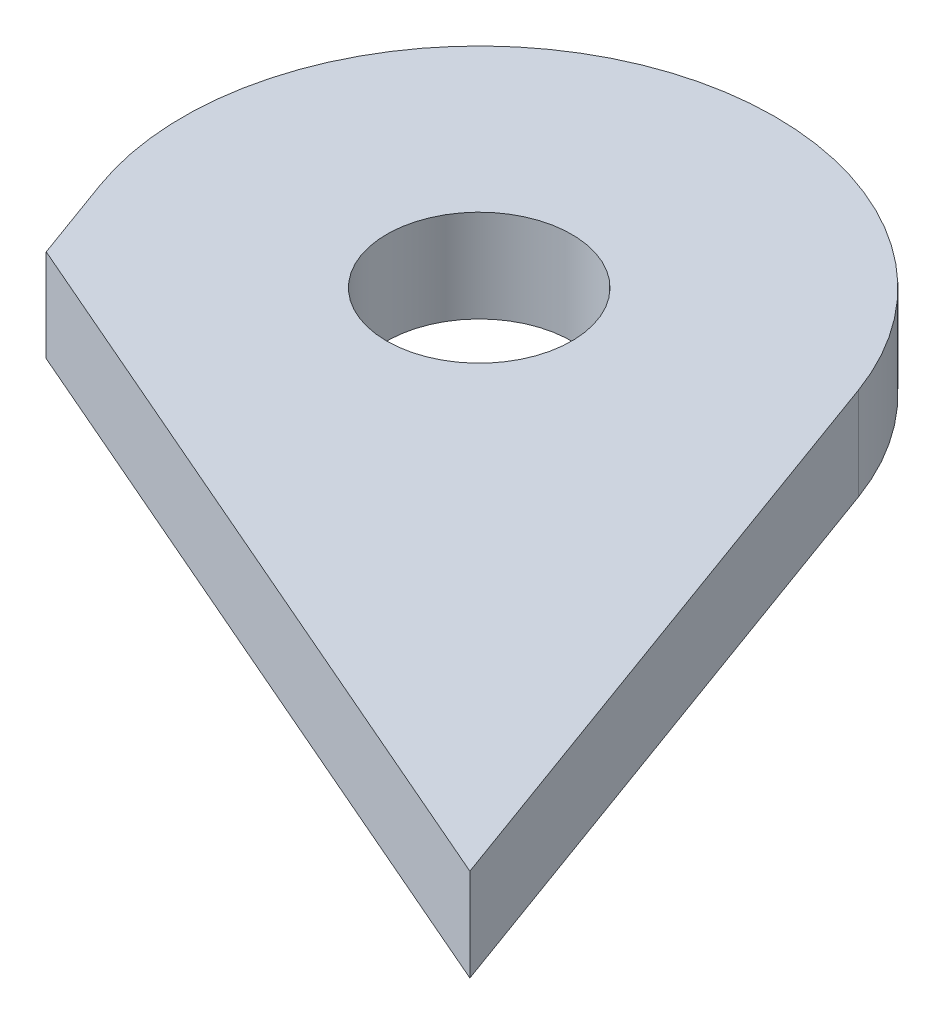
SolidWorks part; units mm, degrees
ref_plane "Front Plane" through (0, 0, 0) normal (0, 0, 1) x (1, 0, 0)
ref_plane "Top Plane" through (0, 0, 0) normal (0, 1, 0) x (1, 0, 0)
ref_plane "Right Plane" through (0, 0, 0) normal (1, 0, 0) x (0, 0, -1)
sketch "Sketch1" plane through (0, 0, 0) normal (0, 1, 0) x (1, 0, 0)
  line L5 (19.0946, 6.9498) -> (-22.2251, -8.0893) construction
  line L6 (19.0946, 6.9498) -> (34.3655, -35.0068)
  line L7 (-968.2745, -35.0068) -> (49031.7255, -35.0068) construction
  line L8 (34.3655, -35.0068) -> (-16.9909, -12.7296)
  line L9 (-19.0946, -6.9498) -> (-16.9909, -12.7296)
  circle A2 centre (0, 0) radius 6.35
  arc A4 (19.0946, 6.9498) -> (-19.0946, -6.9498) centre (0, 0) ccw
  point P3 (8.6873, -23.8682)
  point P5 (0, 0)
  dimension "D1" = 12.7
  dimension "D2" = 13.97
  dimension "D3" = 70
  dimension "D4" = 23.45
  dimension "D5" = 25.4
extrude "Boss-Extrude1" add sketch "Sketch1" along normal blind 6.35
